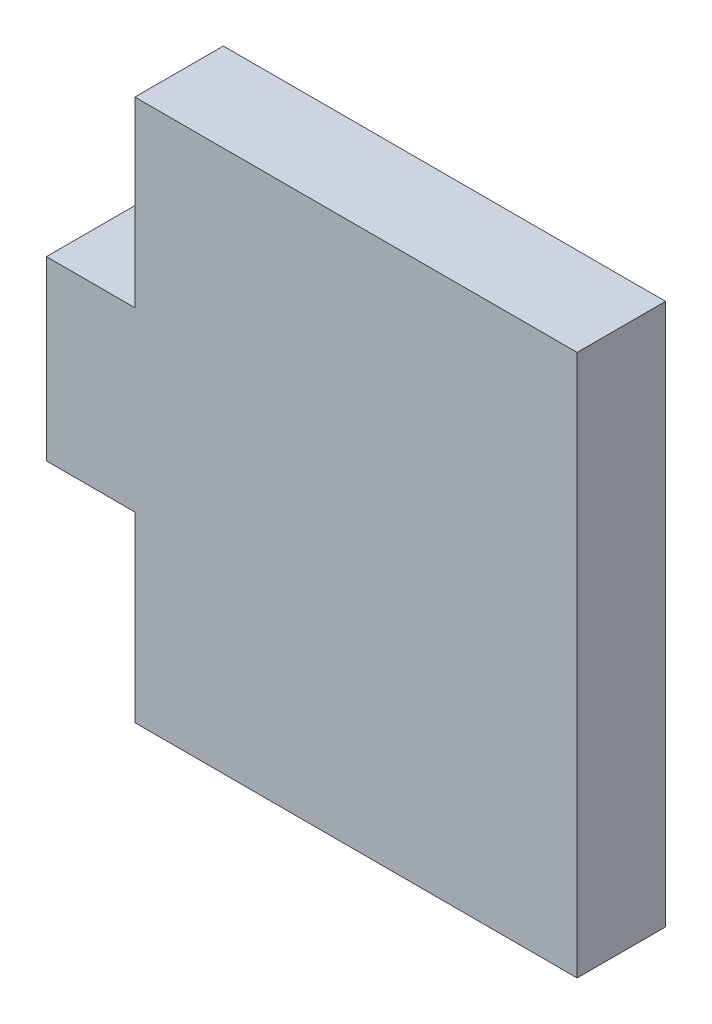
SolidWorks part; units mm, degrees
ref_plane "Alzado" through (0, 0, 0) normal (0, 0, 1) x (1, 0, 0)
ref_plane "Planta" through (0, 0, 0) normal (0, 1, 0) x (1, 0, 0)
ref_plane "Vista lateral" through (0, 0, 0) normal (1, 0, 0) x (0, 0, -1)
sketch "Croquis1" plane through (0, 0, 0) normal (0, 0, 1) x (1, 0, 0)
  line L0 (-12, 0) -> (12, 0) construction
  line L1 (12, 12.25) -> (-8, 12.25)
  line L2 (12, 12.25) -> (12, -12.25)
  line L3 (12, -12.25) -> (-8, -12.25)
  line L4 (-12, 4) -> (-12, -4)
  line L5 (12, 12.25) -> (-8, -8.1667) construction
  line L6 (12, -12.25) -> (-8, 8.1667) construction
  line L9 (-12, 4) -> (-8, 4)
  line L10 (-8, 4) -> (-8, 12.25)
  line L11 (-8, -4) -> (-12, -4)
  line L12 (-8, -4) -> (-8, -12.25)
  point P0 (0, 0)
  dimension "D1" = 24.5
  dimension "D2" = 8.25
  dimension "D3" = 8
  dimension "D4" = 20
extrude "Saliente-Extruir1" add sketch "Croquis1" along normal blind 4
